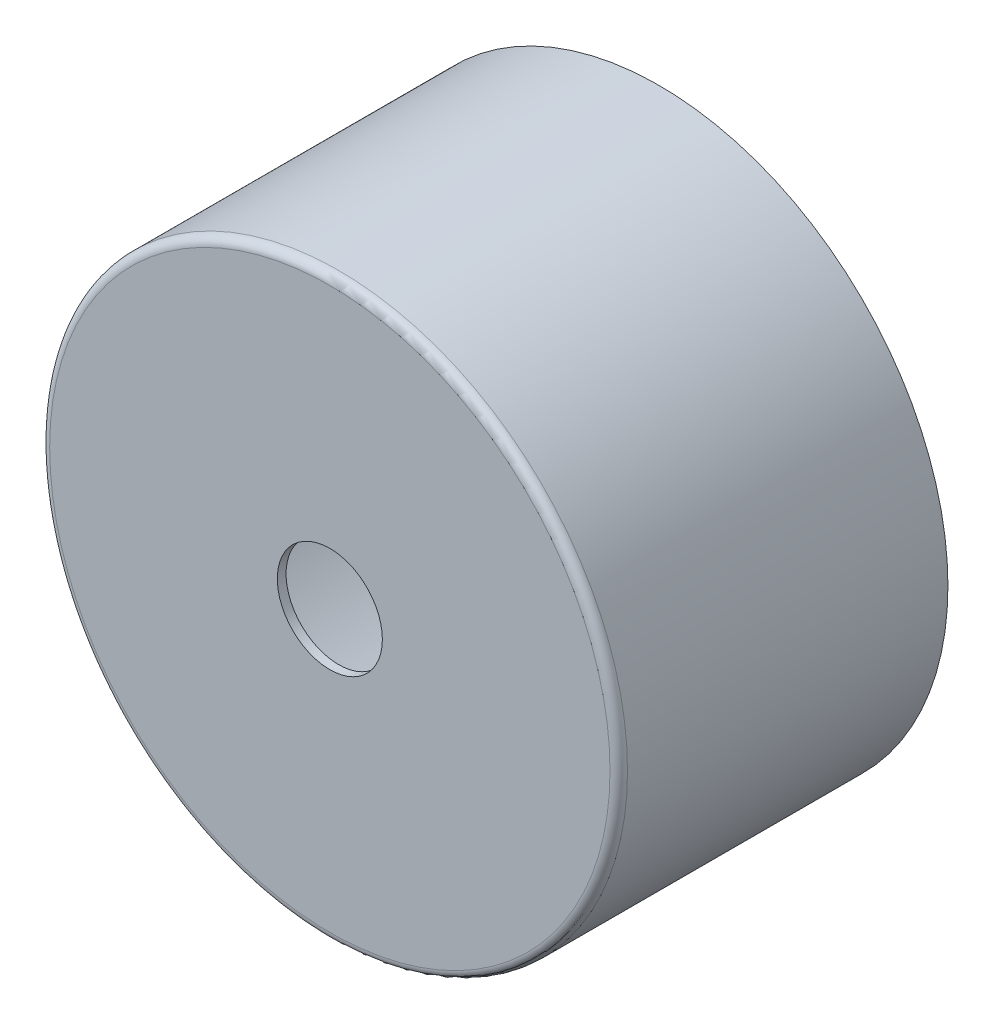
SolidWorks part; units mm, degrees
ref_plane "Front Plane" through (0, 0, 0) normal (0, 0, 1) x (1, 0, 0)
ref_plane "Top Plane" through (0, 0, 0) normal (0, 1, 0) x (1, 0, 0)
ref_plane "Right Plane" through (0, 0, 0) normal (1, 0, 0) x (0, 0, -1)
sketch "Sketch1" plane through (0, 0, 0) normal (0, 0, 1) x (1, 0, 0)
  circle A0 centre (0, 0) radius 16.5
  dimension "D1" = 33
extrude "Boss-Extrude1" add sketch "Sketch1" against normal blind 18.8
shell "Shell1" thickness 0.5
sketch "Sketch2" plane through (0, 0, 0) normal (0, 0, 1) x (1, 0, 0)
  circle A0 centre (0, 0) radius 3
  dimension "D1" = 6
extrude "Cut-Extrude1" cut sketch "Sketch2" against normal through all
fillet "Fillet1" radius 0.5 1 edges at (16.5, 0, 0)
